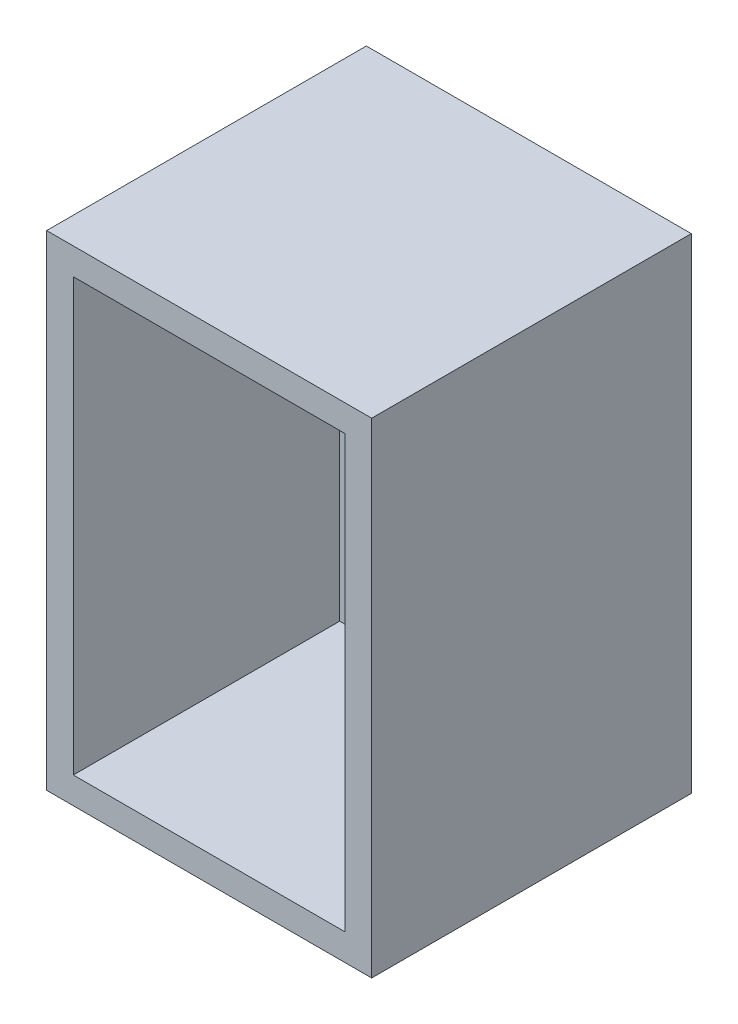
SolidWorks part; units mm, degrees
ref_plane "Front Plane" through (0, 0, 0) normal (0, 0, 1) x (1, 0, 0)
ref_plane "Top Plane" through (0, 0, 0) normal (0, 1, 0) x (1, 0, 0)
ref_plane "Right Plane" through (0, 0, 0) normal (1, 0, 0) x (0, 0, -1)
sketch "Sketch1" plane through (0, 0, 0) normal (0, 0, 1) x (1, 0, 0)
  line L0 (30.5, 45.5) -> (-30.5, 45.5)
  line L1 (25.5, -40.5) -> (-25.5, -40.5)
  line L2 (25.5, -40.5) -> (25.5, 40.5)
  line L3 (25.5, 40.5) -> (-25.5, 40.5)
  line L4 (-25.5, -40.5) -> (-25.5, 40.5)
  line L5 (25.5, -40.5) -> (-25.5, 40.5) construction
  line L6 (25.5, 40.5) -> (-25.5, -40.5) construction
  line L7 (-30.5, -45.5) -> (-30.5, 45.5)
  line L8 (30.5, -45.5) -> (-30.5, -45.5)
  line L9 (30.5, -45.5) -> (30.5, 45.5)
  point P0 (0, 0)
  dimension "D1" = 51
  dimension "D2" = 81
  dimension "D3" = 5
extrude "Boss-Extrude1" add sketch "Sketch1" along normal blind 50
sketch "Sketch2" plane through (0, 0, 0) normal (0, 0, -1) x (-1, 0, 0)
  line L1 (30.5, -45.5) -> (-30.5, -45.5)
  line L2 (30.5, -45.5) -> (30.5, 45.5)
  line L3 (30.5, 45.5) -> (-30.5, 45.5)
  line L4 (-30.5, -45.5) -> (-30.5, 45.5)
  line L5 (30.5, -45.5) -> (-30.5, 45.5) construction
  line L6 (30.5, 45.5) -> (-30.5, -45.5) construction
  point P0 (0, 0)
extrude "Boss-Extrude2" add sketch "Sketch2" along normal blind 10
sketch "Sketch3" plane through (0, 0, -10) normal (0, 0, -1) x (-1, 0, 0)
  line L0 (0, -45.5) -> (0, -25) construction
  line L1 (-30.5, -45.5) -> (30.5, -45.5) construction
  circle A0 centre (0, -25) radius 5
  dimension "D1" = 10
  dimension "D2" = 20.5
extrude "Cut-Extrude1" cut sketch "Sketch3" against normal blind 10
